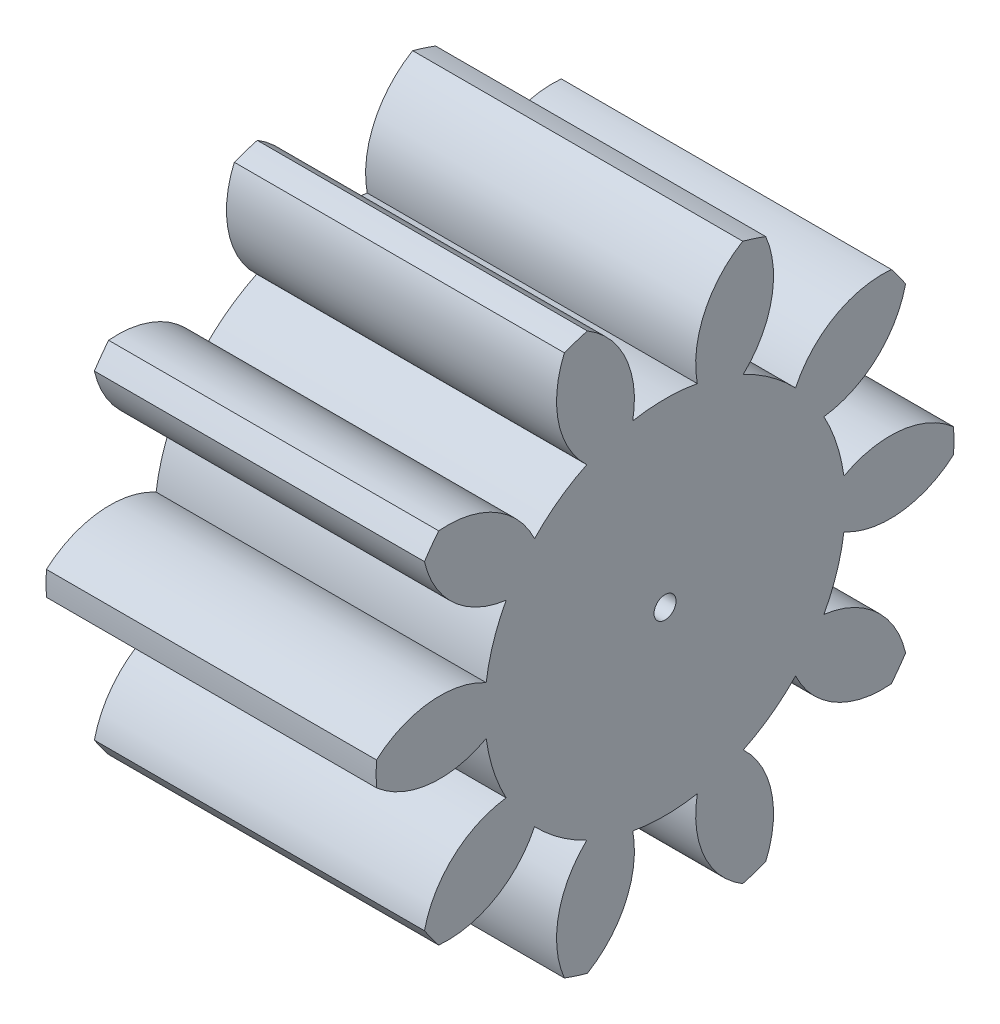
SolidWorks part; units mm, degrees
ref_plane "Plane1" through (0, 0, 0) normal (0, 0, 1) x (1, 0, 0)
ref_plane "Plane2" through (0, 0, 0) normal (0, 1, 0) x (1, 0, 0)
ref_plane "Plane3" through (0, 0, 0) normal (1, 0, 0) x (0, 0, -1)
sketch "HoldingSke" plane through (0, 0, 0) normal (0, 1, 0) x (1, 0, 0)
  line L0 (0, 0) -> (0.5627, -0.0992)
  line L1 (-15, 0) -> (100, 0) construction
  line L2 (0, 0) -> (-2.1039, 2.3779)
  line L3 (0, 0) -> (-11.863, 4.5341)
  line L4 (0, 0) -> (8.5048, 1.4996)
  line L5 (0, 0) -> (-46.8476, -17.4728)
  line L6 (0, 0) -> (-9.9476, -6.7116)
  line L7 (-2.1039, 2.3779) -> (8.6586, 51.2059)
  line L8 (-76.2, 54.61) -> (-76.1, 54.61)
  line L9 (-67.7845, 28.3722) -> (-49.3413, 33.142)
  line L10 (-76.2, 71.12) -> (104.1128, 71.12)
  line L11 (0, 0) -> (-12, 0)
  line L12 (-76.2, 101.6) -> (-76.147, 101.6)
  line L13 (24.9733, 27.94) -> (52.9518, 28.4284)
  line L14 (24.9733, 27.94) -> (24.9743, 27.94)
  line L15 (24.9733, 27.94) -> (100.4006, 29.5858)
  line L16 (-63.627, -1.75) -> (-12.827, -1.75)
  circle A0 centre (0, 0) radius 0.4
  circle A1 centre (0, 0) radius 6.5615
  circle A2 centre (0, 0) radius 37.5
  circle A3 centre (0, 0) radius 0.4
  dimension "MHD" = 13.123
  dimension "Hub_dia" = 75
  dimension "Bore" = 0.8
  dimension "MBD" = 0.8
  dimension "Num_teeth" = 10
  dimension "Pitch" = 0.5714
  dimension "Overall_len" = 50
  dimension "Show_teeth" = 10
  dimension "Thickness" = 12
  dimension "OAL" = 50.0001
  dimension "T_dim" = 0.1
  dimension "Ap" = 14.5
  dimension "H" = 19.05
  dimension "Pitch_radius" = 180.3128
  dimension "Width" = 12
  dimension "Backlash" = 0.053
  dimension "Addendum_fac" = 1
  dimension "Dedendum_fac" = 1.25
  dimension "Clearance_fac" = 0.25
  dimension "Dedendum_add" = 0.001
  dimension "Module" = 1.75
sketch "BasProSke" plane through (0, 0, 0) normal (0, 1, 0) x (1, 0, 0)
  line L0 (-10, 0) -> (60, 0) construction
  line L1 (0, 0) -> (0, 10.5)
  line L2 (0, 0) -> (12, 0)
  line L3 (12, 0) -> (12, 10.5)
  line L4 (12, 10.5) -> (0, 10.5)
  dimension "Thickness" = 12
  dimension "Diameter" = 21
revolve "Base-Revolve" add sketch "BasProSke" angle 360 about L0
sketch "TooCutSke" plane through (0, 0, 0) normal (1, 0, 0) x (0, 0, -1)
  line L1 (0, 0) -> (0, 107) construction
  line L2 (0, 0) -> (-1.4614, 8.6271) construction
  line L3 (0, 0) -> (-5.35, 16.4656) construction
  line L4 (-1.4614, 8.6271) -> (-2.675, 8.2328) construction
  arc A0 (1.1739, 6.4556) -> (-1.1739, 6.4556) centre (0, 0) ccw
  arc A1 (2.8542, 10.131) -> (-2.8542, 10.131) centre (0, 0) ccw
  circle A2 centre (0, 0) radius 8.75 construction
  circle A3 centre (0, 0) radius 8.4713 construction
  arc A4 (-1.1739, 6.4556) -> (-2.8542, 10.131) centre (-4.6131, 7.1051) ccw
  arc A5 (2.8542, 10.131) -> (1.1739, 6.4556) centre (4.6131, 7.1051) ccw
  dimension "Root_dia" = 13.123
  dimension "Overcut_dia" = 21.0508
  dimension "Pitch_dia" = 17.5
  dimension "Base_dia" = 16.9426
  dimension "Flank_rad" = 3.5
  dimension "Half_ang" = 18
  dimension "Half_CT" = 1.2761
extrude "ToothCut" cut sketch "TooCutSke" along normal through all
fillet "Breaks" [suppressed] radius 0.035
fillet "RootFillets" [suppressed] radius 0.4385
pattern_circular "TeethCuts" count 10 every 36 about axis through (-10, 0, 0) along (1, 0, 0) of "ToothCut", "RootFillets", "Breaks"
sketch "HubNeaOneSke" plane through (0, 0, 0) normal (-1, 0, 0) x (0, 0, 1)
  circle A0 centre (0, 0) radius 6.5615
  dimension "Diameter" = 13.123
extrude "HubNearOne" [suppressed] add sketch "HubNeaOneSke" along normal blind 38.0001
sketch "HubNeaBotSke" plane through (0, 0, 0) normal (-1, 0, 0) x (0, 0, 1)
  circle A0 centre (0, 0) radius 6.5615
  dimension "Diameter" = 13.123
extrude "HubNearBoth" [suppressed] add sketch "HubNeaBotSke" along normal blind 19
ref_plane "FarPln" through (12, 0, 0) normal (1, 0, 0) x (0, 0, -1)
sketch "HubFarSke" plane through (12, 0, 0) normal (1, 0, 0) x (0, 0, -1)
  circle A0 centre (0, 0) radius 6.5615
  dimension "Diameter" = 13.123
extrude "HubFar" [suppressed] add sketch "HubFarSke" along normal blind 19
sketch "BorSke" plane through (0, 0, 0) normal (1, 0, 0) x (0, 0, -1)
  circle A0 centre (0, 0) radius 0.4
  dimension "Diameter" = 0.8
extrude "Bore" cut sketch "BorSke" along normal mid plane 100.0001
sketch "KeySke" plane through (0, 0, 0) normal (1, 0, 0) x (0, 0, -1)
  line L0 (-0.05, 0) -> (-0.05, 0.5)
  line L1 (-0.05, 0.5) -> (0.05, 0.5)
  line L2 (0.05, 0.5) -> (0.05, 0)
  line L3 (0, 0) -> (0, 34) construction
  line L4 (-0.05, 0) -> (0.05, 0)
  dimension "Offset" = 0.5
  dimension "Width" = 0.1
extrude "Keyway" [suppressed] cut sketch "KeySke" along normal mid plane 100.0001
pattern_circular "Keyway2" [suppressed] count 2 every 90 about axis through (-10, 0, 0) along (1, 0, 0)
equation "' \"Module@HoldingSke\" = 6.35"
equation "' \"Num_teeth@HoldingSke\" = 12"
equation "' \"Ap@HoldingSke\" =  20"
equation "' \"Ap@HoldingSke\" = 20"
equation "' \"Width@HoldingSke\" = 0.5 * 25.4"
equation "' \"Hub_dia@HoldingSke\"= 1 * 25.4"
equation "' \"Hub_dia@HoldingSke\" = 1 * 25.4"
equation "' \"Overall_len@HoldingSke\" = 1.0 * 25.4"
equation "' \"Bore@HoldingSke\" = 0.75 * 25.4"
equation "' \"T_dim@HoldingSke\" = 0.1 * 25.4"
equation "' \"Width@KeySke\" = 0.25 * 25.4"
equation "' \"Show_teeth@HoldingSke\" = 13"
equation "' \"Backlash@HoldingSke\" = 0.009 * 25.4"
equation "' \"Addendum_fac@HoldingSke\" = 1.0"
equation "' \"Dedendum_fac@HoldingSke\" = 1.25"
equation "' \"Dedendum_add@HoldingSke\" = 0.00005 * 25.4"
equation "' \"Clearance_fac@HoldingSke\" = 0.25"
equation "\"Pitch@HoldingSke\" = 1 / \"Module@HoldingSke\""
equation "\"Overcut_dia@TooCutSke\" = (\"Num_teeth@HoldingSke\" + 2 * \"Addendum_fac@HoldingSke\") / \"Pitch@HoldingSke\" + 0.002 * 25.4"
equation "\"Pitch_dia@TooCutSke\" = \"Num_teeth@HoldingSke\" / \"Pitch@HoldingSke\""
equation "\"Base_dia@TooCutSke\" = \"Num_teeth@HoldingSke\" / \"Pitch@HoldingSke\" * cos((\"Ap@HoldingSke\"  * 3.14159265 / 180))"
equation "\"Root_dia@TooCutSke\" = (\"Num_teeth@HoldingSke\" + 2) / \"Pitch@HoldingSke\" - 2 * (\"Addendum_fac@HoldingSke\" + \"Dedendum_fac@HoldingSke\") / \"Pitch@HoldingSke\" - \"Dedendum_add@HoldingSke\" * 2"
equation "\"Half_ang@TooCutSke\" = 180 / \"Num_teeth@HoldingSke\""
equation "\"Half_CT@TooCutSke\" = \"Num_teeth@HoldingSke\" / \"Pitch@HoldingSke\" * sin((3.14159265 / 2 / \"Num_teeth@HoldingSke\")) / 2 - 7 * \"Backlash@HoldingSke\" / 4"
equation "\"Flank_rad@TooCutSke\" = \"Num_teeth@HoldingSke\" / \"Pitch@HoldingSke\" / 5"
equation "\"Radius@RootFillets\" = \"Clearance_fac@HoldingSke\" / \"Pitch@HoldingSke\" + \"Dedendum_add@HoldingSke\""
equation "\"Break_rad@Breaks\" = 0.02 / \"Pitch@HoldingSke\""
equation "\"Thickness@HoldingSke\" = \"Width@HoldingSke\""
equation "\"OAL@HoldingSke\" = \"Thickness@HoldingSke\""
equation "\"MHD@HoldingSke\" = (\"Num_teeth@HoldingSke\" + 2) / \"Pitch@HoldingSke\" - 2 * (\"Addendum_fac@HoldingSke\" + \"Dedendum_fac@HoldingSke\")  / \"Pitch@HoldingSke\" - \"Dedendum_add@HoldingSke\" * 2"
equation "\"MBD@HoldingSke\" = (\"Num_teeth@HoldingSke\" + 2) / \"Pitch@HoldingSke\" - 2 * (\"Addendum_fac@HoldingSke\" + \"Dedendum_fac@HoldingSke\")  / \"Pitch@HoldingSke\" - \"Dedendum_add@HoldingSke\" * 2 - 0.002 * 25.4"
equation "\"MHD@HoldingSke\" = ((sgn( \"MHD@HoldingSke\" - \"Hub_dia@HoldingSke\" )-1)*( \"MHD@HoldingSke\" - \"Hub_dia@HoldingSke\" ))/-2+ \"Hub_dia@HoldingSke\""
equation "\"MBD@HoldingSke\" = ((sgn( \"MBD@HoldingSke\" - \"Bore@HoldingSke\" )-1)*( \"MBD@HoldingSke\" - \"Bore@HoldingSke\" ))/-2+ \"Bore@HoldingSke\""
equation "\"OAL@HoldingSke\" = ((sgn( \"OAL@HoldingSke\" - \"Overall_len@HoldingSke\" )+1)*( \"OAL@HoldingSke\" - \"Overall_len@HoldingSke\" ))/2 + \"Overall_len@HoldingSke\" + 0.000002 * 25.4"
equation "\"Num_teeth@TeethCuts\" = int( \"Show_teeth@HoldingSke\" ) + 1"
equation "\"Num_teeth@TeethCuts\" = ((sgn( \"Num_teeth@TeethCuts\" - \"Num_teeth@HoldingSke\" )-1)*( \"Num_teeth@TeethCuts\" - \"Num_teeth@HoldingSke\" ))/-2+ \"Num_teeth@HoldingSke\""
equation "\"Num_teeth@TeethCuts\" = ((sgn( \"Num_teeth@TeethCuts\" - 2.0)+1)*( \"Num_teeth@TeethCuts\" - 2.0))/2 +2.0"
equation "\"Angle@TeethCuts\" = 360.0 / \"Num_teeth@HoldingSke\""
equation "\"Diameter@BasProSke\" = (\"Num_teeth@HoldingSke\" + 2 * \"Addendum_fac@HoldingSke\") / \"Pitch@HoldingSke\""
equation "\"Thickness@BasProSke\"  = \"Thickness@HoldingSke\""
equation "' \"Fillet_rad@BasProSke\" =  \"Thickness@HoldingSke\" * 0.05"
equation "' \"Fillet_rad@BasProSke\" = \"Thickness@HoldingSke\" * 0.05"
equation "\"MHD@HoldingSke\" = ((sgn( \"MHD@HoldingSke\" - \"Root_dia@TooCutSke\" )-1)*( \"MHD@HoldingSke\" - \"Root_dia@TooCutSke\" ))/-2+ \"Root_dia@TooCutSke\""
equation "\"Diameter@HubNeaOneSke\" = \"MHD@HoldingSke\""
equation "\"Length@HubNearOne\" = \"OAL@HoldingSke\" - \"Thickness@BasProSke\""
equation "\"Diameter@HubNeaBotSke\" = \"MHD@HoldingSke\""
equation "\"Length@HubNearBoth\" = ( \"OAL@HoldingSke\" - \"Thickness@BasProSke\" ) / 2.0"
equation "\"Thickness@FarPln\" = \"Thickness@BasProSke\""
equation "\"Diameter@HubFarSke\" = \"MHD@HoldingSke\""
equation "\"Length@HubFar\" = ( \"OAL@HoldingSke\" - \"Thickness@BasProSke\" ) / 2.0"
equation "\"Diameter@BorSke\" = \"MBD@HoldingSke\""
equation "\"D1@Bore\" = \"OAL@HoldingSke\" * 2.0"
equation "\"D1@Keyway\" = \"OAL@HoldingSke\" * 2.0"
equation "\"Offset@KeySke\" = \"T_dim@HoldingSke\" + \"MBD@HoldingSke\" / 2.0"
